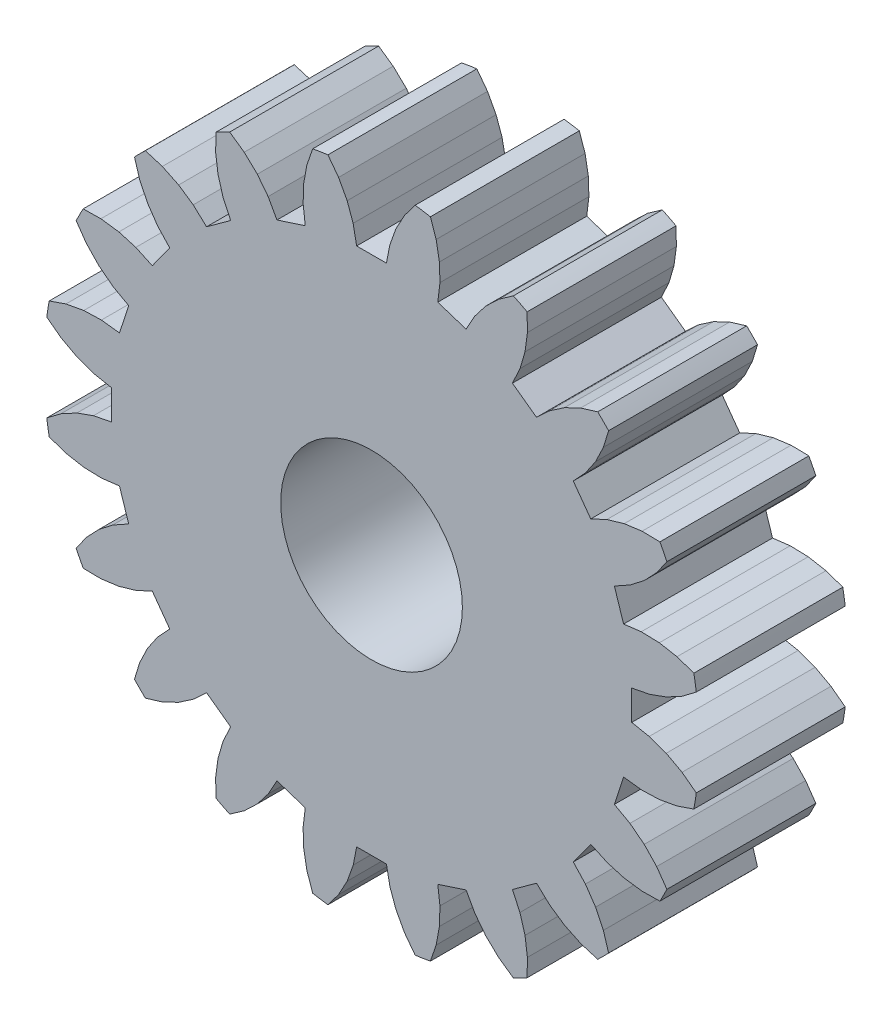
SolidWorks part; units mm, degrees
ref_plane "Alzado" through (0, 0, 0) normal (0, 0, 1) x (1, 0, 0)
ref_plane "Planta" through (0, 0, 0) normal (0, 1, 0) x (1, 0, 0)
ref_plane "Vista lateral" through (0, 0, 0) normal (1, 0, 0) x (0, 0, -1)
sketch "Croquis1" plane through (0, 0, 0) normal (0, 0, 1) x (1, 0, 0)
  line L0 (-0.4418, 0.3705) -> (-0.4418, 2.8705) construction
  circle A1 centre (-0.4418, 0.3705) radius 11
  circle A2 centre (-0.4418, 0.3705) radius 3.05
  point P7 (5.5386, 6.7727)
  point P9 (5.5386, 6.7727)
  dimension "D1" = 6.1
extrude "Saliente-Extruir1" add sketch "Croquis1" along normal blind 5
sketch "Croquis6" plane through (0, 0, 5) normal (0, 0, 1) x (1, 0, 0)
  line L0 (6.3309, 5.9091) -> (6.9186, 5.1002)
  line L1 (6.9186, 5.1002) -> (7.4601, 5.3523)
  line L2 (7.4601, 5.3523) -> (8.0415, 5.5228)
  line L3 (8.0415, 5.5228) -> (8.6403, 5.6034)
  line L4 (8.6403, 5.6034) -> (9.2392, 5.5934)
  line L5 (9.2392, 5.5934) -> (8.9398, 6.6146)
  line L6 (8.9398, 6.6146) -> (8.3409, 7.4389)
  line L7 (8.3409, 7.4389) -> (7.5171, 7.9637)
  line L8 (7.5171, 7.9637) -> (7.3429, 7.3946)
  line L9 (7.3429, 7.3946) -> (7.0798, 6.8464)
  line L10 (7.0798, 6.8464) -> (6.7466, 6.3569)
  line L11 (6.7466, 6.3569) -> (6.3309, 5.9091)
  line L12 (8.2447, 3.8426) -> (7.7109, 3.5451)
  line L13 (8.7128, 4.2052) -> (8.2447, 3.8426)
  line L14 (9.1324, 4.6452) -> (8.7128, 4.2052)
  line L15 (9.474, 5.1327) -> (9.1324, 4.6452)
  line L16 (10.0953, 4.3789) -> (9.474, 5.1327)
  line L17 (9.8129, 2.5407) -> (10.3793, 2.3462)
  line L18 (9.2184, 2.6491) -> (9.8129, 2.5407)
  line L19 (8.6128, 2.6667) -> (9.2184, 2.6491)
  line L20 (8.0199, 2.5942) -> (8.6128, 2.6667)
  line L21 (7.7109, 3.5451) -> (8.0199, 2.5942)
  line L22 (10.3793, 2.3462) -> (10.4101, 3.41)
  line L23 (10.4101, 3.41) -> (10.0953, 4.3789)
  line L24 (8.8924, 0.9884) -> (8.2929, 0.8704)
  line L25 (9.4498, 1.1886) -> (8.8924, 0.9884)
  line L26 (9.9848, 1.4774) -> (9.4498, 1.1886)
  line L27 (10.4602, 1.8355) -> (9.9848, 1.4774)
  line L28 (10.8183, 0.9266) -> (10.4602, 1.8355)
  line L29 (9.9816, -0.7343) -> (10.4602, -1.0945)
  line L30 (9.4498, -0.4476) -> (9.9816, -0.7343)
  line L31 (8.8792, -0.2437) -> (9.4498, -0.4476)
  line L32 (8.2929, -0.1294) -> (8.8792, -0.2437)
  line L33 (8.2929, 0.8704) -> (8.2929, -0.1294)
  line L34 (10.4602, -1.0945) -> (10.8183, -0.0922)
  line L35 (10.8183, -0.0922) -> (10.8183, 0.9266)
  line L36 (8.6265, -1.9263) -> (8.0199, -1.8532)
  line L37 (9.2184, -1.9081) -> (8.6265, -1.9263)
  line L38 (9.8165, -1.7988) -> (9.2184, -1.9081)
  line L39 (10.3793, -1.6052) -> (9.8165, -1.7988)
  line L40 (10.439, -2.5802) -> (10.3793, -1.6052)
  line L41 (9.13, -3.9013) -> (9.474, -4.3917)
  line L42 (8.7128, -3.4642) -> (9.13, -3.9013)
  line L43 (8.2332, -3.094) -> (8.7128, -3.4642)
  line L44 (7.7109, -2.8041) -> (8.2332, -3.094)
  line L45 (8.0199, -1.8532) -> (7.7109, -2.8041)
  line L46 (9.474, -4.3917) -> (10.1242, -3.5491)
  line L47 (10.1242, -3.5491) -> (10.439, -2.5802)
  line L48 (7.4729, -4.6161) -> (6.9186, -4.3592)
  line L49 (8.0415, -4.7818) -> (7.4729, -4.6161)
  line L50 (8.6441, -4.8626) -> (8.0415, -4.7818)
  line L51 (9.2392, -4.8524) -> (8.6441, -4.8626)
  line L52 (8.9947, -5.7981) -> (9.2392, -4.8524)
  line L53 (7.3415, -6.6501) -> (7.5171, -7.2227)
  line L54 (7.0798, -6.1054) -> (7.3415, -6.6501)
  line L55 (6.738, -5.6052) -> (7.0798, -6.1054)
  line L56 (6.3309, -5.1681) -> (6.738, -5.6052)
  line L57 (6.9186, -4.3592) -> (6.3309, -5.1681)
  line L58 (7.5171, -7.2227) -> (8.3958, -6.6223)
  line L59 (8.3958, -6.6223) -> (8.9947, -5.7981)
  line L60 (5.5446, -6.8179) -> (5.0968, -6.4022)
  line L61 (6.0342, -7.1511) -> (5.5446, -6.8179)
  line L62 (6.5823, -7.4142) -> (6.0342, -7.1511)
  line L63 (7.1514, -7.5883) -> (6.5823, -7.4142)
  line L64 (6.6266, -8.4122) -> (7.1514, -7.5883)
  line L65 (4.7911, -8.7116) -> (4.7811, -9.3105)
  line L66 (4.7105, -8.1128) -> (4.7911, -8.7116)
  line L67 (4.54, -7.5314) -> (4.7105, -8.1128)
  line L68 (4.2879, -6.9899) -> (4.54, -7.5314)
  line L69 (5.0968, -6.4022) -> (4.2879, -6.9899)
  line L70 (4.7811, -9.3105) -> (5.8024, -9.0111)
  line L71 (5.8024, -9.0111) -> (6.6266, -8.4122)
  line L72 (3.0303, -8.3159) -> (2.7328, -7.7822)
  line L73 (3.3929, -8.7841) -> (3.0303, -8.3159)
  line L74 (3.8329, -9.2037) -> (3.3929, -8.7841)
  line L75 (4.3204, -9.5452) -> (3.8329, -9.2037)
  line L76 (3.5667, -10.1666) -> (4.3204, -9.5452)
  line L77 (1.7285, -9.8842) -> (1.5339, -10.4506)
  line L78 (1.8369, -9.2897) -> (1.7285, -9.8842)
  line L79 (1.8544, -8.6841) -> (1.8369, -9.2897)
  line L80 (1.7819, -8.0912) -> (1.8544, -8.6841)
  line L81 (2.7328, -7.7822) -> (1.7819, -8.0912)
  line L82 (1.5339, -10.4506) -> (2.5977, -10.4814)
  line L83 (2.5977, -10.4814) -> (3.5667, -10.1666)
  line L84 (0.1761, -8.9637) -> (0.0581, -8.3642)
  line L85 (0.3763, -9.5211) -> (0.1761, -8.9637)
  line L86 (0.6651, -10.0561) -> (0.3763, -9.5211)
  line L87 (1.0232, -10.5315) -> (0.6651, -10.0561)
  line L88 (0.1143, -10.8895) -> (1.0232, -10.5315)
  line L89 (-1.5466, -10.0529) -> (-1.9067, -10.5315)
  line L90 (-1.2598, -9.5211) -> (-1.5466, -10.0529)
  line L91 (-1.056, -8.9505) -> (-1.2598, -9.5211)
  line L92 (-0.9417, -8.3642) -> (-1.056, -8.9505)
  line L93 (0.0581, -8.3642) -> (-0.9417, -8.3642)
  line L94 (-1.9067, -10.5315) -> (-0.9045, -10.8895)
  line L95 (-0.9045, -10.8895) -> (0.1143, -10.8895)
  line L96 (-2.7386, -8.6978) -> (-2.6655, -8.0912)
  line L97 (-2.7204, -9.2897) -> (-2.7386, -8.6978)
  line L98 (-2.6111, -9.8878) -> (-2.7204, -9.2897)
  line L99 (-2.4174, -10.4506) -> (-2.6111, -9.8878)
  line L100 (-3.3924, -10.5103) -> (-2.4174, -10.4506)
  line L101 (-4.7136, -9.2013) -> (-5.2039, -9.5452)
  line L102 (-4.2765, -8.7841) -> (-4.7136, -9.2013)
  line L103 (-3.9063, -8.3045) -> (-4.2765, -8.7841)
  line L104 (-3.6164, -7.7822) -> (-3.9063, -8.3045)
  line L105 (-2.6655, -8.0912) -> (-3.6164, -7.7822)
  line L106 (-5.2039, -9.5452) -> (-4.3614, -10.1955)
  line L107 (-4.3614, -10.1955) -> (-3.3924, -10.5103)
  line L108 (-5.4284, -7.5442) -> (-5.1715, -6.9899)
  line L109 (-5.5941, -8.1128) -> (-5.4284, -7.5442)
  line L110 (-5.6749, -8.7154) -> (-5.5941, -8.1128)
  line L111 (-5.6647, -9.3105) -> (-5.6749, -8.7154)
  line L112 (-6.6104, -9.0659) -> (-5.6647, -9.3105)
  line L113 (-7.4623, -7.4128) -> (-8.035, -7.5883)
  line L114 (-6.9177, -7.1511) -> (-7.4623, -7.4128)
  line L115 (-6.4175, -6.8093) -> (-6.9177, -7.1511)
  line L116 (-5.9804, -6.4022) -> (-6.4175, -6.8093)
  line L117 (-5.1715, -6.9899) -> (-5.9804, -6.4022)
  line L118 (-8.035, -7.5883) -> (-7.4346, -8.4671)
  line L119 (-7.4346, -8.4671) -> (-6.6104, -9.0659)
  line L120 (-7.6301, -5.6159) -> (-7.2145, -5.1681)
  line L121 (-7.9634, -6.1054) -> (-7.6301, -5.6159)
  line L122 (-8.2265, -6.6536) -> (-7.9634, -6.1054)
  line L123 (-8.4006, -7.2227) -> (-8.2265, -6.6536)
  line L124 (-9.2245, -6.6979) -> (-8.4006, -7.2227)
  line L125 (-9.5239, -4.8624) -> (-10.1228, -4.8524)
  line L126 (-8.9251, -4.7818) -> (-9.5239, -4.8624)
  line L127 (-8.3437, -4.6113) -> (-8.9251, -4.7818)
  line L128 (-7.8022, -4.3592) -> (-8.3437, -4.6113)
  line L129 (-7.2145, -5.1681) -> (-7.8022, -4.3592)
  line L130 (-10.1228, -4.8524) -> (-9.8233, -5.8736)
  line L131 (-9.8233, -5.8736) -> (-9.2245, -6.6979)
  line L132 (-9.1282, -3.1016) -> (-8.5945, -2.8041)
  line L133 (-9.5964, -3.4642) -> (-9.1282, -3.1016)
  line L134 (-10.016, -3.9042) -> (-9.5964, -3.4642)
  line L135 (-10.3575, -4.3917) -> (-10.016, -3.9042)
  line L136 (-10.9789, -3.6379) -> (-10.3575, -4.3917)
  line L137 (-10.6964, -1.7997) -> (-11.2629, -1.6052)
  line L138 (-10.102, -1.9081) -> (-10.6964, -1.7997)
  line L139 (-9.4964, -1.9257) -> (-10.102, -1.9081)
  line L140 (-8.9035, -1.8532) -> (-9.4964, -1.9257)
  line L141 (-8.5945, -2.8041) -> (-8.9035, -1.8532)
  line L142 (-11.2629, -1.6052) -> (-11.2937, -2.669)
  line L143 (-11.2937, -2.669) -> (-10.9789, -3.6379)
  line L144 (-9.776, -0.2474) -> (-9.1765, -0.1294)
  line L145 (-10.3333, -0.4476) -> (-9.776, -0.2474)
  line L146 (-10.8684, -0.7364) -> (-10.3333, -0.4476)
  line L147 (-11.3438, -1.0945) -> (-10.8684, -0.7364)
  line L148 (-11.7018, -0.1856) -> (-11.3438, -1.0945)
  line L149 (-10.8652, 1.4753) -> (-11.3438, 1.8355)
  line L150 (-10.3333, 1.1886) -> (-10.8652, 1.4753)
  line L151 (-9.7628, 0.9847) -> (-10.3333, 1.1886)
  line L152 (-9.1765, 0.8704) -> (-9.7628, 0.9847)
  line L153 (-9.1765, -0.1294) -> (-9.1765, 0.8704)
  line L154 (-11.3438, 1.8355) -> (-11.7018, 0.8332)
  line L155 (-11.7018, 0.8332) -> (-11.7018, -0.1856)
  line L156 (-9.5101, 2.6673) -> (-8.9035, 2.5942)
  line L157 (-10.102, 2.6491) -> (-9.5101, 2.6673)
  line L158 (-10.7001, 2.5398) -> (-10.102, 2.6491)
  line L159 (-11.2629, 2.3462) -> (-10.7001, 2.5398)
  line L160 (-11.3226, 3.3212) -> (-11.2629, 2.3462)
  line L161 (-10.0136, 4.6423) -> (-10.3575, 5.1327)
  line L162 (-9.5964, 4.2052) -> (-10.0136, 4.6423)
  line L163 (-9.1168, 3.835) -> (-9.5964, 4.2052)
  line L164 (-8.5945, 3.5451) -> (-9.1168, 3.835)
  line L165 (-8.9035, 2.5942) -> (-8.5945, 3.5451)
  line L166 (-10.3575, 5.1327) -> (-11.0077, 4.2901)
  line L167 (-11.0077, 4.2901) -> (-11.3226, 3.3212)
  line L168 (-8.3565, 5.3571) -> (-7.8022, 5.1002)
  line L169 (-8.9251, 5.5228) -> (-8.3565, 5.3571)
  line L170 (-9.5277, 5.6036) -> (-8.9251, 5.5228)
  line L171 (-10.1228, 5.5934) -> (-9.5277, 5.6036)
  line L172 (-9.8782, 6.5391) -> (-10.1228, 5.5934)
  line L173 (-8.2251, 7.3911) -> (-8.4006, 7.9637)
  line L174 (-7.9634, 6.8464) -> (-8.2251, 7.3911)
  line L175 (-7.6216, 6.3462) -> (-7.9634, 6.8464)
  line L176 (-7.2145, 5.9091) -> (-7.6216, 6.3462)
  line L177 (-7.8022, 5.1002) -> (-7.2145, 5.9091)
  line L178 (-8.4006, 7.9637) -> (-9.2794, 7.3633)
  line L179 (-9.2794, 7.3633) -> (-9.8782, 6.5391)
  line L180 (-6.4282, 7.5589) -> (-5.9804, 7.1432)
  line L181 (-6.9177, 7.8921) -> (-6.4282, 7.5589)
  line L182 (-7.4659, 8.1552) -> (-6.9177, 7.8921)
  line L183 (-8.035, 8.3293) -> (-7.4659, 8.1552)
  line L184 (-7.5102, 9.1532) -> (-8.035, 8.3293)
  line L185 (-5.6747, 9.4526) -> (-5.6647, 10.0515)
  line L186 (-5.5941, 8.8538) -> (-5.6747, 9.4526)
  line L187 (-5.4236, 8.2724) -> (-5.5941, 8.8538)
  line L188 (-5.1715, 7.7309) -> (-5.4236, 8.2724)
  line L189 (-5.9804, 7.1432) -> (-5.1715, 7.7309)
  line L190 (-5.6647, 10.0515) -> (-6.6859, 9.7521)
  line L191 (-6.6859, 9.7521) -> (-7.5102, 9.1532)
  line L192 (-3.9139, 9.0569) -> (-3.6164, 8.5232)
  line L193 (-4.2765, 9.5251) -> (-3.9139, 9.0569)
  line L194 (-4.7165, 9.9447) -> (-4.2765, 9.5251)
  line L195 (-5.2039, 10.2862) -> (-4.7165, 9.9447)
  line L196 (-4.4502, 10.9076) -> (-5.2039, 10.2862)
  line L197 (-2.612, 10.6252) -> (-2.4174, 11.1916)
  line L198 (-2.7204, 10.0307) -> (-2.612, 10.6252)
  line L199 (-2.738, 9.4251) -> (-2.7204, 10.0307)
  line L200 (-2.6655, 8.8322) -> (-2.738, 9.4251)
  line L201 (-3.6164, 8.5232) -> (-2.6655, 8.8322)
  line L202 (-2.4174, 11.1916) -> (-3.4812, 11.2224)
  line L203 (-3.4812, 11.2224) -> (-4.4502, 10.9076)
  line L204 (-1.0597, 9.7047) -> (-0.9417, 9.1052)
  line L205 (-1.2598, 10.2621) -> (-1.0597, 9.7047)
  line L206 (-1.5487, 10.7971) -> (-1.2598, 10.2621)
  line L207 (-1.9067, 11.2725) -> (-1.5487, 10.7971)
  line L208 (-0.9979, 11.6305) -> (-1.9067, 11.2725)
  line L209 (0.6631, 10.7939) -> (1.0232, 11.2725)
  line L210 (0.3763, 10.2621) -> (0.6631, 10.7939)
  line L211 (0.1725, 9.6915) -> (0.3763, 10.2621)
  line L212 (0.0581, 9.1052) -> (0.1725, 9.6915)
  line L213 (-0.9417, 9.1052) -> (0.0581, 9.1052)
  line L214 (1.0232, 11.2725) -> (0.0209, 11.6305)
  line L215 (0.0209, 11.6305) -> (-0.9979, 11.6305)
  line L216 (1.855, 9.4388) -> (1.7819, 8.8322)
  line L217 (1.8369, 10.0307) -> (1.855, 9.4388)
  line L218 (1.7275, 10.6288) -> (1.8369, 10.0307)
  line L219 (1.5339, 11.1916) -> (1.7275, 10.6288)
  line L220 (2.5089, 11.2513) -> (1.5339, 11.1916)
  line L221 (3.83, 9.9423) -> (4.3204, 10.2862)
  line L222 (3.3929, 9.5251) -> (3.83, 9.9423)
  line L223 (3.0228, 9.0455) -> (3.3929, 9.5251)
  line L224 (2.7328, 8.5232) -> (3.0228, 9.0455)
  line L225 (1.7819, 8.8322) -> (2.7328, 8.5232)
  line L226 (4.3204, 10.2862) -> (3.4778, 10.9365)
  line L227 (3.4778, 10.9365) -> (2.5089, 11.2513)
  line L228 (4.5449, 8.2852) -> (4.2879, 7.7309)
  line L229 (4.7105, 8.8538) -> (4.5449, 8.2852)
  line L230 (4.7913, 9.4564) -> (4.7105, 8.8538)
  line L231 (4.7811, 10.0515) -> (4.7913, 9.4564)
  line L232 (5.7268, 9.8069) -> (4.7811, 10.0515)
  line L233 (6.5788, 8.1538) -> (7.1514, 8.3293)
  line L234 (6.0342, 7.8921) -> (6.5788, 8.1538)
  line L235 (5.5339, 7.5503) -> (6.0342, 7.8921)
  line L236 (5.0968, 7.1432) -> (5.5339, 7.5503)
  line L237 (4.2879, 7.7309) -> (5.0968, 7.1432)
  line L238 (7.1514, 8.3293) -> (6.5511, 9.2081)
  line L239 (6.5511, 9.2081) -> (5.7268, 9.8069)
  circle A1 centre (-0.4418, 0.3705) radius 11 construction
  point P253 (-0.4418, 0.3705)
  dimension "D1" = 20
extrude "Cortar-Extruir6" cut sketch "Croquis6" against normal blind 5
